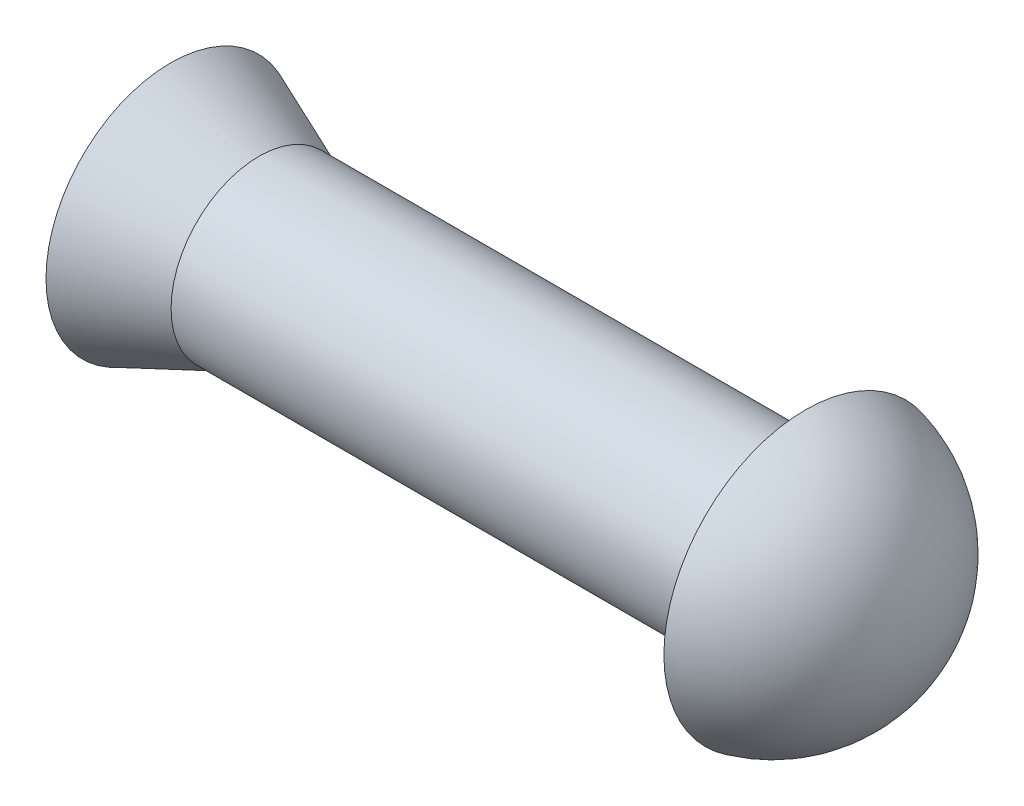
SolidWorks part; units mm, degrees
ref_plane "Plane1" through (0, 0, 0) normal (0, 0, 1) x (1, 0, 0)
ref_plane "Plane2" through (0, 0, 0) normal (0, 1, 0) x (1, 0, 0)
ref_plane "Plane3" through (0, 0, 0) normal (1, 0, 0) x (0, 0, -1)
sketch "Sketch1" plane through (0, 0, 0) normal (0, 0, 1) x (1, 0, 0)
  line L0 (-39, 0) -> (6, 0) construction
  line L1 (-131.9234, 0) -> (0, 0)
  line L2 (-111.8934, 18) -> (-130, 25.5)
  line L3 (-111.8934, 18) -> (0, 18)
  line L4 (0, 18) -> (0, 0)
  line L5 (-111.8934, -18) -> (-130, -25.5) construction
  arc A0 (-130, 25.5) -> (-131.9234, 0) centre (38.0766, 0) ccw
  point P12 (-111.8934, 18)
  dimension "HeadRadius" = 170
  dimension "Diameter" = 36
  dimension "HeadAng" = 45
  dimension "GripLength" = 130
  dimension "HeadDia" = 51
revolve "Base-Revolve" add sketch "Sketch1" angle 360 about L0
sketch "Sketch2" plane through (0, 0, 0) normal (0, 0, 1) x (1, 0, 0)
  line L0 (-49, 0) -> (29, 0) construction
  line L1 (0, 0) -> (23, 0)
  line L2 (0, 0) -> (0, 29)
  arc A0 (23, 0) -> (0, 29) centre (-6.7826, 0) ccw
  dimension "HeadDiaA" = 58
  dimension "HeadHtA" = 23
revolve "HeadTypeA" add sketch "Sketch2" angle 360 about L0
sketch "Sketch3" plane through (0, 0, 0) normal (0, 0, 1) x (1, 0, 0)
  line L0 (10, 0) -> (-136, 0) construction
  line L1 (-39, 0) -> (6, 0) construction
  line L2 (-19.3137, 0) -> (2, 0)
  line L3 (0, 26) -> (-19.3137, 18)
  line L5 (0, -26) -> (-19.3137, -18) construction
  line L6 (-19.3137, 0) -> (-19.3137, 18)
  arc A0 (2, 0) -> (0, 26) centre (-168, 0) ccw
  dimension "D1" = 170
  dimension "HeadDiaB" = 52
  dimension "D3" = 36
  dimension "D2" = 45
revolve "HeadTypeB" [suppressed] add sketch "Sketch3" angle 360 about L0
equation "\"D3@Sketch3\" = \"Diameter@Sketch1\""
equation "\"D2@Sketch3\" = \"HeadAng@Sketch1\""
equation "\"D1@Sketch3\" = \"HeadRadius@Sketch1\""
